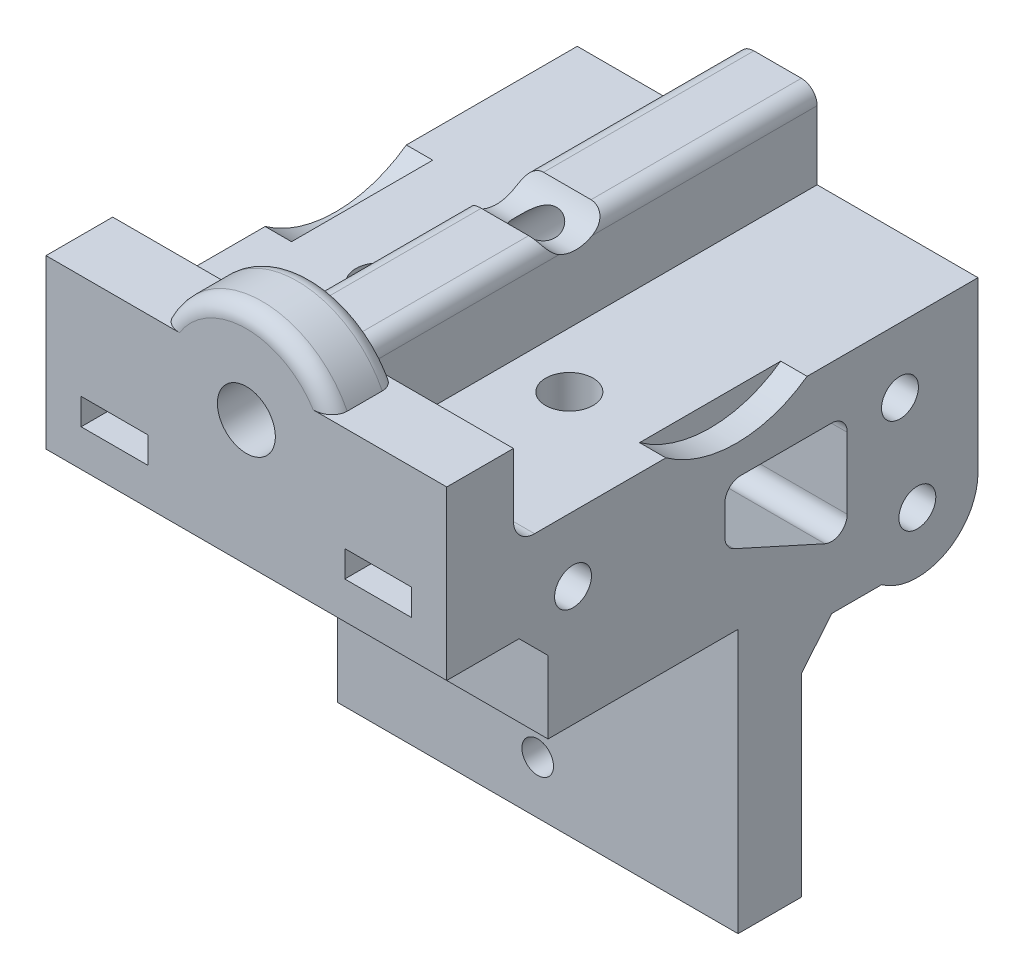
SolidWorks part; units mm, degrees
ref_plane "Front Plane" through (0, 0, 0) normal (0, 0, 1) x (1, 0, 0)
ref_plane "Top Plane" through (0, 0, 0) normal (0, 1, 0) x (1, 0, 0)
ref_plane "Right Plane" through (0, 0, 0) normal (1, 0, 0) x (0, 0, -1)
sketch "Sketch10" plane through (0, 0, 0) normal (1, 0, 0) x (0, 0, -1)
  line L0 (-27.4459, 9.6079) -> (-20.588, 9.6079)
  line L1 (-17.838, 0) -> (0.18, 0)
  line L2 (-21.12, 17.5) -> (-21.12, 25.5)
  line L3 (-21.12, 17.5) -> (22.93, 17.5)
  line L5 (-21.12, 25.5) -> (-27.4459, 25.5)
  line L6 (0.18, 0) -> (0.18, -25)
  line L7 (0.18, -25) -> (6.18, -25)
  line L8 (6.18, -6.6486) -> (6.18, -25)
  line L9 (9.0676, -3.1486) -> (13.7958, -3.1486)
  line L10 (6.18, -6.6486) -> (9.0676, -3.1486)
  line L11 (22.93, 1.5) -> (22.93, 17.5)
  line L12 (-27.4459, 9.6079) -> (-27.4459, 25.5)
  line L13 (-20.588, 9.6079) -> (-17.838, 6.8579)
  line L14 (-17.838, 6.8579) -> (-17.838, 0)
  arc A0 (13.7958, -3.1486) -> (22.93, 1.5) centre (17.18, 1.5) ccw
  point P1 (-17.838, 9.6079)
  dimension "D6" = 5.75
  dimension "D1" = 6
  dimension "D2" = 33.6259
  dimension "D3" = 17.5
  dimension "D4" = 8
  dimension "D5" = 3.5
  dimension "D9" = 25
extrude "Boss-Extrude5" add sketch "Sketch10" along normal mid plane 38
sketch "Sketch18" plane through (0, 17.5, 0) normal (0, 1, 0) x (1, 0, 0)
  line L0 (19, 22.93) -> (-19, 22.93) construction
  line L2 (-3.75, 22.93) -> (3.75, 22.93)
  line L3 (-3.75, 22.93) -> (-3.75, 14.93)
  line L4 (19, 22.93) -> (19, -21.12) construction
  line L5 (19, -21.12) -> (-19, -21.12) construction
  line L7 (-3.75, -21.12) -> (3.75, -21.12)
  line L8 (-3.75, -21.12) -> (-3.75, 14.93)
  line L12 (3.75, -21.12) -> (3.75, 22.93)
  line L14 (-19, 22.93) -> (-19, -21.12) construction
extrude "Boss-Extrude6" add sketch "Sketch18" along normal blind 8
sketch "Sketch21" plane through (0, 0, 27.4459) normal (0, 0, -1) x (-1, 0, 0)
  line L0 (8.0623, 25.5) -> (-8.0623, 25.5)
  line L1 (0, 25.5) -> (0, -25) construction
  line L2 (-19, 25.5) -> (19, 25.5) construction
  line L3 (-19, -25) -> (19, -25) construction
  arc A0 (8.0623, 25.5) -> (-8.0623, 25.5) centre (0, 21.5) ccw
  dimension "D2" = 9
  dimension "D1" = 4
extrude "Boss-Extrude7" add sketch "Sketch21" along normal up to surface (6.3259 mm away) up to face at (11.375, 21.5, 21.12)
sketch "Sketch11" plane through (0, 0, 0) normal (1, 0, 0) x (0, 0, -1)
  line L0 (22.93, 1.5) -> (22.93, 17.5) construction
  line L2 (-17.838, 0) -> (0.18, 0) construction
  circle A0 centre (-15.47, 11.35) radius 1.75
  circle A1 centre (15.53, 11.35) radius 1.75
  circle A2 centre (17.18, 1.5) radius 1.75
  dimension "D4" = 3.5
  dimension "D5" = 3.5
  dimension "D1" = 31
  dimension "D2" = 11.35
  dimension "D3" = 7.4
extrude "Cut-Motor" cut sketch "Sketch11" against normal mid plane 38
sketch "Sketch12" plane through (0, 0, -0.18) normal (0, 0, 1) x (1, 0, 0)
  line L0 (4.5, -10) -> (0, -20) construction
  line L1 (0, -20) -> (-4.5, -10) construction
  line L2 (-4.5, -10) -> (4.5, -10) construction
  line L3 (19, 0) -> (-19, 0) construction
  circle A0 centre (0, -20) radius 1.5
  circle A1 centre (4.5, -10) radius 1.5
  circle A2 centre (-4.5, -10) radius 1.5
  dimension "D1" = 3
  dimension "D2" = 9
  dimension "D3" = 10
  dimension "D4" = 10
extrude "Cut-Extrude7" cut sketch "Sketch12" against normal through all
sketch "Sketch13" plane through (0, 0, 0) normal (0, -1, 0) x (1, 0, 0)
  line L1 (19, -0.18) -> (-19, -0.18) construction
  circle A0 centre (-9, 5.82) radius 2.25
  circle A1 centre (9, 5.82) radius 2.25
  dimension "D1" = 4.5
  dimension "D2" = 18
  dimension "D3" = 6
extrude "Cut-Extrude8" cut sketch "Sketch13" against normal through all
sketch "Sketch14" plane through (0, 0, 0) normal (0, -1, 0) x (1, 0, 0)
  circle A0 centre (9, 5.82) radius 5.5
  circle A1 centre (-9, 5.82) radius 5.5
  dimension "D1" = 11
extrude "Cut-Extrude9" cut sketch "Sketch14" against normal blind 4 contours A1 | A0
sketch "Sketch16" plane through (-19, 0, 0) normal (-1, 0, 0) x (0, 0, 1)
  line L1 (-22.93, 1.5) -> (-22.93, 17.5) construction
  circle A0 centre (-0.03, 26.85) radius 11.5
  circle A3 centre (-15.53, 11.35) radius 1.75 construction
  dimension "D1" = 22.9
  dimension "D2" = 15.5
extrude "Cut-Motor-L" cut sketch "Sketch16" against normal blind 2.5
sketch "Sketch15" plane through (19, 0, 0) normal (1, 0, 0) x (0, 0, -1)
  circle A0 centre (0.03, 26.85) radius 11.5
  arc A1 (-6.6653, 17.5) -> (6.7253, 17.5) centre (0.03, 26.85) ccw construction
extrude "Cut-Motor-R" cut sketch "Sketch15" against normal blind 2.5
sketch "Sketch19" plane through (3.75, 0, 0) normal (1, 0, 0) x (0, 0, -1)
  circle A0 centre (0.03, 26.85) radius 3.25
  dimension "D1" = 6.5
extrude "Cut-Extrude10" cut sketch "Sketch19" against normal blind 8
sketch "Sketch20" plane through (0, 0, -22.93) normal (0, 0, 1) x (1, 0, 0)
  circle A0 centre (0, 21.5) radius 2.75
  dimension "D1" = 5.5
extrude "Cut-Extrude11" cut sketch "Sketch20" along normal through all
sketch "Sketch22" plane through (19, 0, 0) normal (1, 0, 0) x (0, 0, -1)
  line L0 (-0.1886, 6.8011) -> (8.4114, 2.9077)
  line L1 (-3.57, 4) -> (-3.57, 17.5) construction
  line L2 (-1.07, 8.1675) -> (-1.07, 11)
  line L3 (0.43, 12.5) -> (9.03, 12.5)
  line L4 (10.53, 4.2741) -> (10.53, 11)
  line L5 (6.7253, 17.5) -> (-6.6653, 17.5) construction
  arc A0 (8.4114, 2.9077) -> (10.53, 4.2741) centre (9.03, 4.2741) ccw
  arc A1 (-0.1886, 6.8011) -> (-1.07, 8.1675) centre (0.43, 8.1675) cw
  arc A2 (-1.07, 11) -> (0.43, 12.5) centre (0.43, 11) cw
  arc A3 (9.03, 12.5) -> (10.53, 11) centre (9.03, 11) cw
  circle A4 centre (15.53, 11.35) radius 1.75 construction
  dimension "D1" = 1.5
  dimension "D2" = 2.5
  dimension "D3" = 5
  dimension "D4" = 5
extrude "Cut-Extrude12" cut sketch "Sketch22" against normal through all contours L0 A0 L4 A3 L3 A2 L2 A1
fillet "Fillet1" radius 2 2 edges at (-11.375, 17.5, 21.12) (11.375, 17.5, 21.12)
fillet "Fillet2" radius 1.5 2 edges at (0, 30.5, 21.12) (0, 30.5, 27.4459)
fillet "Fillet3" radius 1.5 4 edges at (3.75, 25.5, -12.9582) (-3.75, 25.5, 12.0232) (-3.75, 25.5, -12.9582) (3.75, 25.5, 12.0232)
sketch "Sketch24" plane through (0, 9.6079, 0) normal (0, -1, 0) x (1, 0, 0)
  line L0 (0, 27.4459) -> (0, 17.82) construction
  line L4 (19, 27.4459) -> (-19, 27.4459) construction
  circle A0 centre (-12.5, 22.4459) radius 1.75
  circle A1 centre (12.5, 22.4459) radius 1.75
  point P10 (0, 0)
  point P11 (0, 0)
  point P12 (0, 0)
  point P13 (0, 0)
  point P14 (-12.3442, 23.5495)
  point P15 (12.9806, 23.5495)
  point P16 (0, 0)
  point P17 (0, 0)
  point P18 (0, 0)
  point P19 (-15.1497, 26.586)
  dimension "D4" = 3.5
  dimension "D1" = 25
  dimension "D2" = 12.5
  dimension "D3" = 5
extrude "Cut-Extrude14" cut sketch "Sketch24" against normal blind 6
sketch "Sketch25" plane through (0, 15.6079, 0) normal (0, -1, 0) x (1, 0, 0)
  line L0 (-15.6679, 27.4459) -> (-9.3321, 27.4459)
  line L1 (19, 27.4459) -> (-19, 27.4459) construction
  line L2 (-15.6679, 27.4459) -> (-15.6679, 20.6169)
  line L3 (-15.6679, 20.6169) -> (-12.5, 18.7879)
  line L4 (-12.5, 18.7879) -> (-9.3321, 20.6169)
  line L5 (-9.3321, 20.6169) -> (-9.3321, 27.4459)
  line L6 (9.3321, 27.4459) -> (15.6679, 27.4459)
  line L8 (9.3321, 27.4459) -> (9.3321, 20.6169)
  line L9 (9.3321, 20.6169) -> (12.5, 18.7879)
  line L10 (12.5, 18.7879) -> (15.6679, 20.6169)
  line L11 (15.6679, 20.6169) -> (15.6679, 27.4459)
  line L13 (-9.3321, 24.2749) -> (-10.916, 25.1894) [skipped]
  line L14 (-14.084, 25.1894) -> (-15.6679, 24.2749) [skipped]
  line L15 (12.5, 26.1039) -> (10.916, 25.1894) [skipped]
  line L16 (15.6679, 24.2749) -> (14.084, 25.1894) [skipped]
  circle A0 centre (-12.5, 22.4459) radius 2.9 construction
  circle A1 centre (12.5, 22.4459) radius 2.9 construction
  dimension "D1" = 5.8
extrude "Cut-Extrude15" cut sketch "Sketch25" along normal blind 2.5
